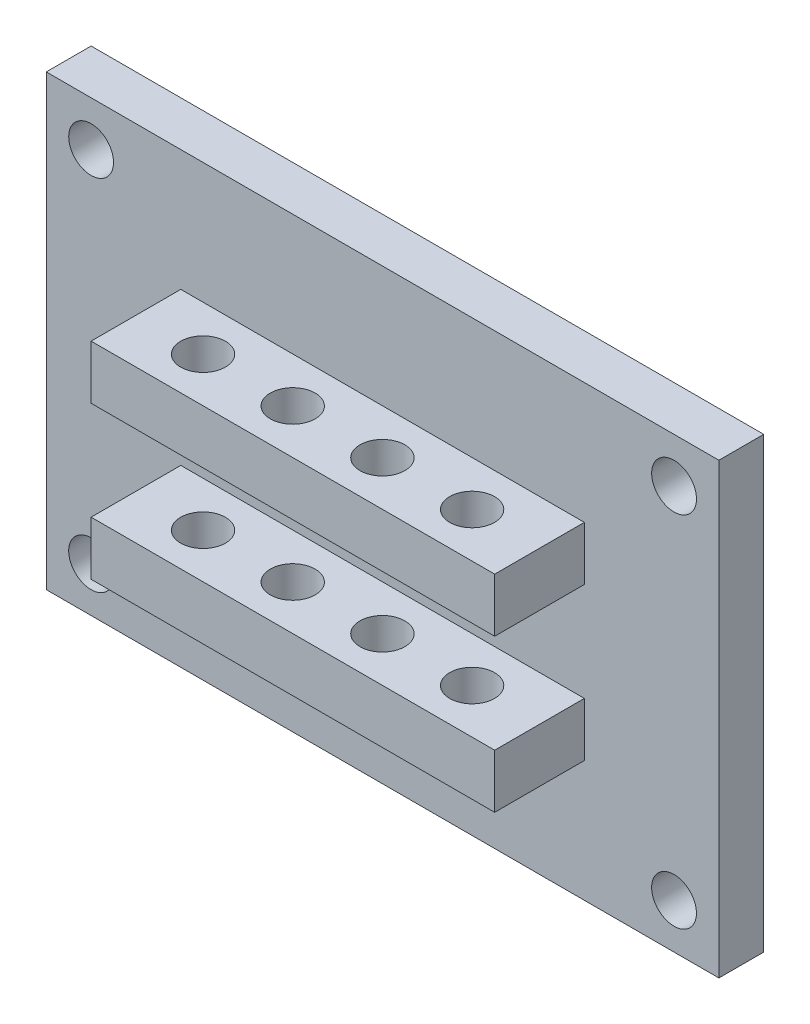
SolidWorks part; units mm, degrees
ref_plane "Plan de face" through (0, 0, 0) normal (0, 0, 1) x (1, 0, 0)
ref_plane "Plan de dessus" through (0, 0, 0) normal (0, 1, 0) x (1, 0, 0)
ref_plane "Plan de droite" through (0, 0, 0) normal (1, 0, 0) x (0, 0, -1)
sketch "Esquisse1" plane through (0, 0, 0) normal (0, 0, 1) x (1, 0, 0)
  line L0 (0, 0) -> (31.3175, 0) construction
  line L1 (-22.5, 11.5) -> (22.5, 11.5)
  line L2 (-22.5, 11.5) -> (-22.5, 5.5)
  line L3 (-22.5, 5.5) -> (22.5, 5.5)
  line L4 (22.5, 11.5) -> (22.5, 5.5)
  line L5 (-22.5, 11.5) -> (22.5, 5.5) construction
  line L6 (-22.5, 5.5) -> (22.5, 11.5) construction
  line L7 (-22.5, -5.5) -> (22.5, -11.5) construction
  line L8 (-22.5, -11.5) -> (22.5, -5.5) construction
  line L9 (22.5, -11.5) -> (22.5, -5.5)
  line L10 (-22.5, -5.5) -> (22.5, -5.5)
  line L11 (-22.5, -11.5) -> (-22.5, -5.5)
  line L12 (-22.5, -11.5) -> (22.5, -11.5)
  point P0 (0, 8.5)
  point P12 (0, -8.5)
  dimension "D1" = 45
  dimension "D2" = 6
  dimension "D3" = 8.5
extrude "Boss.-Extru.1" add sketch "Esquisse1" along normal blind 10
sketch "Esquisse2" plane through (0, 0, 0) normal (0, 0, -1) x (-1, 0, 0)
  line L0 (0, 0) -> (0, 25) construction
  line L1 (-37.5, -25) -> (37.5, -25)
  line L2 (-37.5, -25) -> (-37.5, 25)
  line L3 (-37.5, 25) -> (37.5, 25)
  line L4 (37.5, -25) -> (37.5, 25)
  line L5 (-37.5, -25) -> (37.5, 25) construction
  line L6 (-37.5, 25) -> (37.5, -25) construction
  line L7 (0, 0) -> (37.5, 0) construction
  circle A0 centre (32.5, 20) radius 2.5
  circle A1 centre (-32.5, 20) radius 2.5
  circle A2 centre (-32.5, -20) radius 2.5
  circle A3 centre (32.5, -20) radius 2.5
  point P0 (0, 0)
  dimension "D5" = 5
  dimension "D1" = 50
  dimension "D2" = 75
  dimension "D3" = 5
  dimension "D4" = 5
extrude "Boss.-Extru.2" add sketch "Esquisse2" along normal blind 5
sketch "Esquisse3" plane through (0, -11.5, 0) normal (0, -1, 0) x (1, 0, 0)
  line L0 (0, 0) -> (0, 10) construction
  line L1 (37.5, 0) -> (-37.5, 0) construction
  line L2 (-22.5, 10) -> (22.5, 10) construction
  line L3 (0, 5) -> (-22.5, 5) construction
  line L4 (-22.5, 10) -> (-22.5, 0) construction
  circle A0 centre (-5, 5.0184) radius 2.5
  circle A1 centre (5, 5.0184) radius 2.5
  circle A2 centre (15, 5.0184) radius 2.5
  circle A3 centre (-15, 5.0184) radius 2.5
  dimension "D2" = 5
  dimension "D1" = 5
  dimension "D3" = 3
  dimension "D4" = 2
extrude "Enlèv. mat.-Extru.1" cut sketch "Esquisse3" against normal up to surface (23 mm away) up to face at (0, 11.5, 5)
